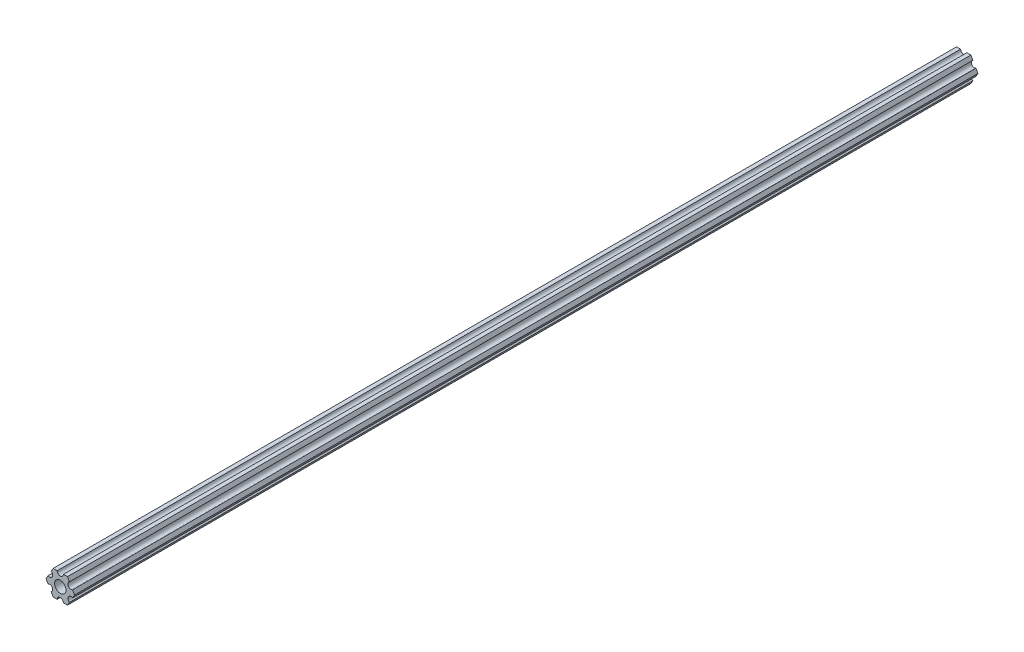
SolidWorks part; units mm, degrees
ref_plane "Front Plane" through (0, 0, 0) normal (0, 0, 1) x (1, 0, 0)
ref_plane "Top Plane" through (0, 0, 0) normal (0, 1, 0) x (1, 0, 0)
ref_plane "Right Plane" through (0, 0, 0) normal (1, 0, 0) x (0, 0, -1)
sketch "Sketch1" plane through (0, 0, 0) normal (0, 0, 1) x (1, 0, 0)
  line L0 (-1.5875, 6.35) -> (-3.6662, 6.35)
  line L1 (7.3323, 0) -> (6.293, 1.8002)
  line L2 (3.6662, 6.35) -> (1.5875, 6.35)
  line L3 (-3.6662, 6.35) -> (-4.7055, 4.5498)
  line L4 (-7.3323, 0) -> (-6.293, -1.8002)
  line L5 (-3.6662, -6.35) -> (-1.5875, -6.35)
  line L6 (3.6662, -6.35) -> (4.7055, -4.5498)
  line L7 (-6.293, 1.8002) -> (-7.3323, 0)
  line L8 (-4.7055, -4.5498) -> (-3.6662, -6.35)
  line L9 (1.5875, -6.35) -> (3.6662, -6.35)
  line L10 (6.293, -1.8002) -> (7.3323, 0)
  line L11 (4.7055, 4.5498) -> (3.6662, 6.35)
  circle A0 centre (0, 0) radius 2.9337
  arc A2 (-1.5875, 6.35) -> (1.5875, 6.35) centre (0, 6.35) ccw
  arc A3 (4.7055, 4.5498) -> (6.293, 1.8002) centre (5.4993, 3.175) ccw
  arc A4 (6.293, -1.8002) -> (4.7055, -4.5498) centre (5.4993, -3.175) ccw
  arc A5 (1.5875, -6.35) -> (-1.5875, -6.35) centre (0, -6.35) ccw
  arc A6 (-4.7055, -4.5498) -> (-6.293, -1.8002) centre (-5.4993, -3.175) ccw
  arc A7 (-6.293, 1.8002) -> (-4.7055, 4.5498) centre (-5.4993, 3.175) ccw
  dimension "D1" = 5.8674
  dimension "D3" = 3.175
  dimension "D4" = 6
extrude "Boss-Extrude1" add sketch "Sketch1" along normal mid plane 463.55
